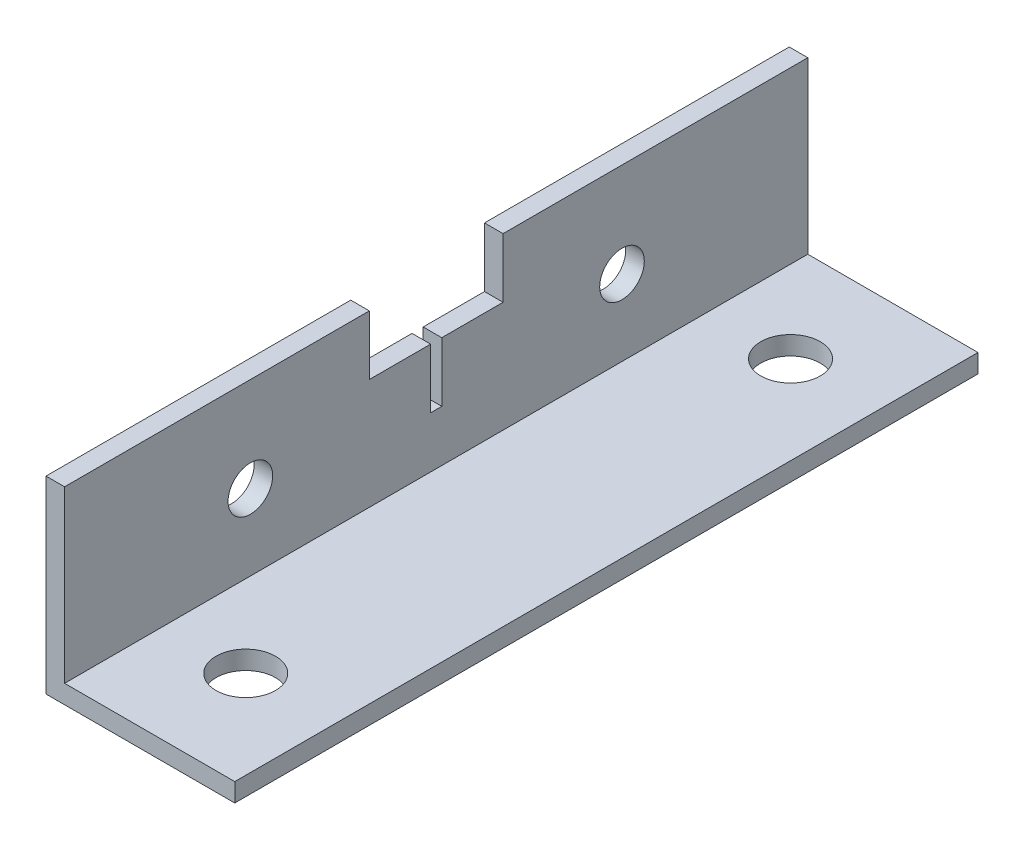
SolidWorks part; units mm, degrees
material "6061-T4 (SS)"
ref_plane "Front Plane" through (0, 0, 0) normal (0, 0, 1) x (1, 0, 0)
ref_plane "Top Plane" through (0, 0, 0) normal (0, 1, 0) x (1, 0, 0)
ref_plane "Right Plane" through (0, 0, 0) normal (1, 0, 0) x (0, 0, -1)
sketch "Sketch1" plane through (0, 0, 0) normal (0, 0, 1) x (1, 0, 0)
  line L0 (0, 0) -> (0, 25.4)
  line L1 (0, 0) -> (25.4, 0)
  dimension "D1" = 25.4
  dimension "D2" = 25.4
extrude "Extrude-Thin1" add sketch "Sketch1" along normal mid plane 100 thin
sketch "Sketch7" plane through (0, 0, 0) normal (-1, 0, 0) x (0, 0, 1)
  line L0 (-50, 12.7) -> (50, 12.7) construction
  line L1 (-50, 25.4) -> (-50, 0) construction
  line L2 (50, 25.4) -> (50, 0) construction
  line L3 (0, 0) -> (0, 25.4) construction
  line L4 (50, 25.4) -> (-50, 25.4) construction
  line L5 (-9, 25.4) -> (-9, 17.4)
  line L6 (-9, 17.4) -> (-0.75, 17.4)
  line L7 (-0.75, 17.4) -> (-0.75, 9.4)
  line L8 (-0.75, 9.4) -> (0.75, 9.4)
  line L9 (-9, 25.4) -> (9, 25.4)
  line L10 (9, 25.4) -> (9, 17.4)
  line L11 (9, 17.4) -> (0.75, 17.4)
  line L12 (0.75, 17.4) -> (0.75, 9.4)
  circle A0 centre (-25, 12.7) radius 3
  circle A1 centre (25, 12.7) radius 3
  point P20 (0, 9.4)
  point P24 (0, 0)
  dimension "D2" = 18
  dimension "D4" = 6
  dimension "D1" = 1.5
  dimension "D3" = 8
  dimension "D5" = 25
  dimension "D6" = 8
extrude "Cut-Extrude5" cut sketch "Sketch7" against normal through all
sketch "Sketch6" plane through (0, 0, 0) normal (0, -1, 0) x (1, 0, 0)
  line L0 (0, 0) -> (25.4, 0) construction
  line L1 (25.4, 50) -> (25.4, -50) construction
  line L2 (13.525, -50) -> (13.525, 50) construction
  line L3 (2.5, -50) -> (25.4, -50) construction
  line L4 (2.5, 50) -> (25.4, 50) construction
  line L6 (0, 50) -> (0, -50) construction
  circle A0 centre (13.525, 36.65) radius 4
  circle A1 centre (13.525, -36.65) radius 4
  dimension "D1" = 8
  dimension "D2" = 73.3
  dimension "D3" = 13.525
extrude "Cut-Extrude4" cut sketch "Sketch6" against normal up to next
